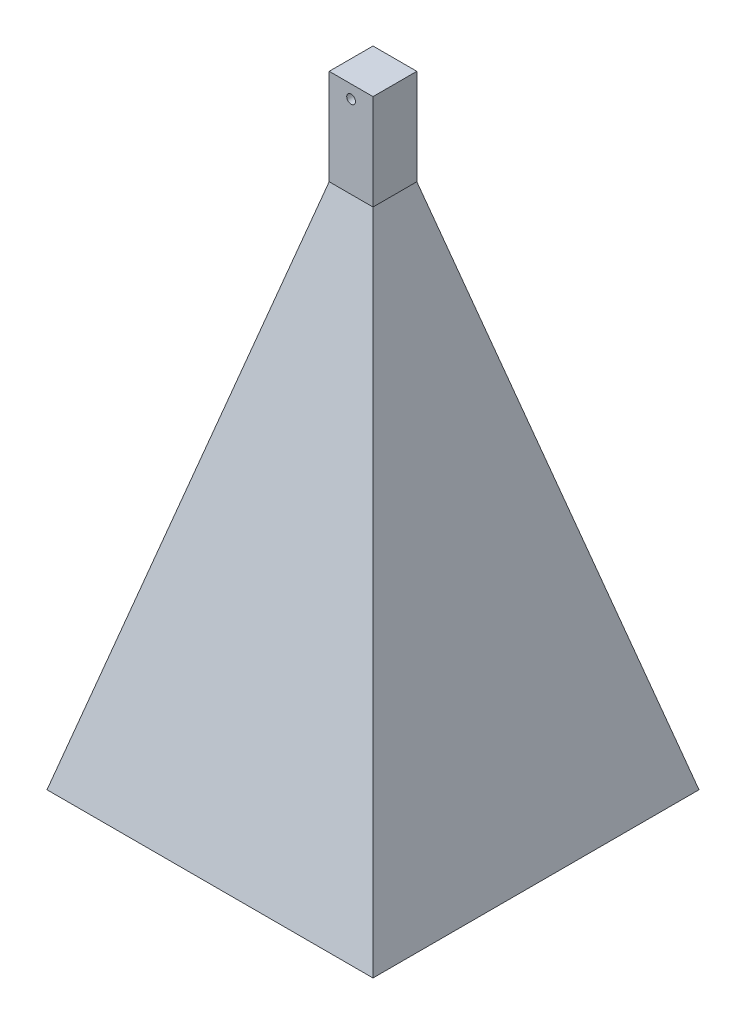
SolidWorks part; units mm, degrees
ref_plane "Front Plane" through (0, 0, 0) normal (0, 0, 1) x (1, 0, 0)
ref_plane "Top Plane" through (0, 0, 0) normal (0, 1, 0) x (1, 0, 0)
ref_plane "Right Plane" through (0, 0, 0) normal (1, 0, 0) x (0, 0, -1)
sketch "Sketch1" plane through (0, 0, 0) normal (0, 1, 0) x (1, 0, 0)
  line L1 (0, 0) -> (744, 0)
  line L2 (0, 0) -> (0, 744)
  line L3 (0, 744) -> (744, 744)
  line L4 (744, 0) -> (744, 744)
  dimension "D1" = 744
  dimension "D2" = 744
extrude "Boss-Extrude1" add sketch "Sketch1" along normal blind 1390 draft 15 contours L2 L1 L4 L3
sketch "Sketch6" plane through (0, 0, 0) normal (0, -1, 0) x (1, 0, 0)
  line L8 (5, -739) -> (739, -739)
  line L9 (739, -739) -> (739, -5)
  line L10 (739, -5) -> (5, -5)
  line L11 (5, -5) -> (5, -739)
  line L12 (5, -739) -> (739, -739)
  line L13 (739, -739) -> (739, -5)
  line L14 (739, -5) -> (5, -5)
  line L15 (5, -5) -> (5, -739)
  dimension "D1" = 5
extrude "Cut-Extrude3" cut sketch "Sketch6" against normal blind 1390 draft 15
ref_plane "Plane3" through (0, 1390, 0) normal (0, 1, 0) x (1, 0, 0)
sketch "Sketch7" plane through (0, 1390, 0) normal (0, 1, 0) x (1, 0, 0)
  line L0 (372, 372) -> (744, 744) construction
  line L1 (322, 322) -> (422, 322)
  line L2 (322, 322) -> (322, 422)
  line L3 (322, 422) -> (422, 422)
  line L4 (422, 322) -> (422, 422)
  line L5 (322, 322) -> (422, 422) construction
  line L6 (322, 422) -> (422, 322) construction
  point P0 (372, 372)
  point P8 (372, 372)
  dimension "D1" = 100
extrude "Boss-Extrude2" add sketch "Sketch7" along normal blind 30 and the other way up to body separate body
sketch "Sketch9" plane through (0, 0, -322) normal (0, 0, 1) x (1, 0, 0)
  line L0 (409.2, 1390) -> (-409.2, 1390) construction
  line L1 (322, 1201.7204) -> (322, 1420) construction
  circle A0 centre (372, 1390) radius 10
  point P8 (379.0467, 1420)
  dimension "D1" = 20
  dimension "D2" = 50
extrude "Cut-Extrude4" cut sketch "Sketch9" against normal blind 70
sketch "Sketch10" plane through (0, 1390, 0) normal (0, 1, 0) x (1, 0, 0)
  line L8 (402, 342) -> (402, 402)
  line L9 (402, 402) -> (342, 402)
  line L10 (342, 402) -> (342, 342)
  line L11 (342, 342) -> (402, 342)
  line L12 (402, 342) -> (402, 402)
  line L13 (402, 402) -> (342, 402)
  line L14 (342, 402) -> (342, 342)
  line L15 (342, 342) -> (402, 342)
  dimension "D1" = 20
extrude "Cut-Extrude5" cut sketch "Sketch10" against normal through all and the other way blind 20
